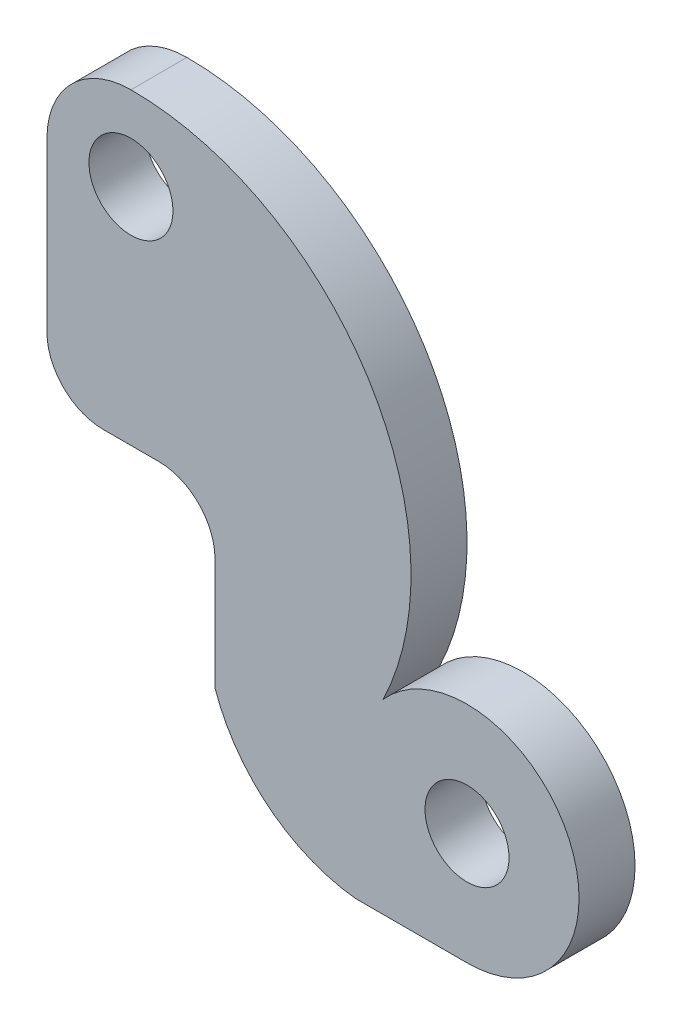
SolidWorks part; units mm, degrees
ref_plane "Front Plane" through (0, 0, 0) normal (0, 0, 1) x (1, 0, 0)
ref_plane "Top Plane" through (0, 0, 0) normal (0, 1, 0) x (1, 0, 0)
ref_plane "Right Plane" through (0, 0, 0) normal (1, 0, 0) x (0, 0, -1)
sketch "Sketch1" plane through (0, 0, 0) normal (0, 0, 1) x (1, 0, 0)
  line L0 (-15, 0) -> (-15, -30)
  line L1 (-5, -40) -> (5, -40)
  line L2 (15, -50) -> (15, -70)
  line L3 (60, -90) -> (40, -90)
  line L4 (40, -70) -> (40, -90) construction
  circle A0 centre (0, 0) radius 7.5
  circle A1 centre (60, -70) radius 7.5
  arc A2 (-15, 0) -> (0, 15) centre (0, 0) cw
  arc A3 (60, -90) -> (45.0248, -56.7431) centre (60, -70) ccw
  arc A4 (0, 15) -> (45.0248, -56.7431) centre (0, -35) cw
  arc A5 (-15, -30) -> (-5, -40) centre (-5, -30) ccw
  arc A6 (5, -40) -> (15, -50) centre (5, -50) cw
  arc A8 (15, -70) -> (40, -90) centre (43.3499, -60.1876) ccw
  point P12 (0, 0)
  point P16 (-15, -40)
  dimension "D1" = 15
  dimension "D2" = 10
  dimension "D5" = 15
  dimension "D6" = 40
  dimension "D7" = 50
  dimension "D8" = 10
  dimension "D10" = 30
  dimension "D9" = 70
  dimension "D11" = 45
  dimension "D13" = 30
  dimension "D3" = 60
  dimension "D4" = 40
  dimension "D12" = 70
extrude "Boss-Extrude1" add sketch "Sketch1" along normal mid plane 10
